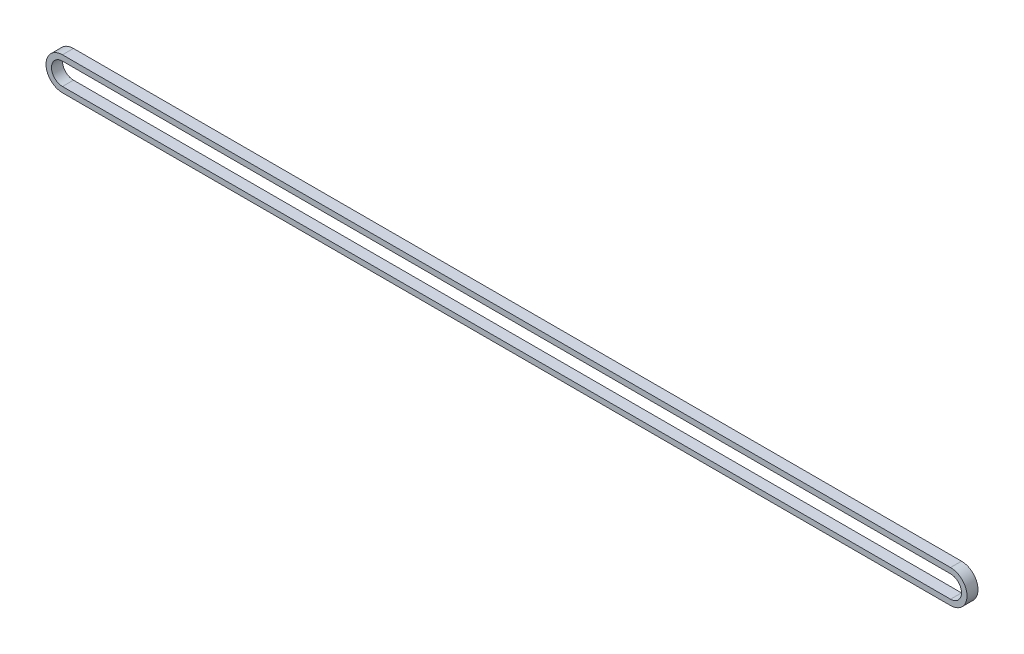
SolidWorks part; units mm, degrees
ref_plane "前视基准面" through (0, 0, 0) normal (0, 0, 1) x (1, 0, 0)
ref_plane "上视基准面" through (0, 0, 0) normal (0, 1, 0) x (1, 0, 0)
ref_plane "右视基准面" through (0, 0, 0) normal (1, 0, 0) x (0, 0, -1)
sketch "Sketch1" plane through (0, 0, 0) normal (0, 0, 1) x (1, 0, 0)
  line L0 (0, 0) -> (0, 35.8552) construction
  line L1 (-242.5, 9) -> (242.5, 9)
  line L2 (242.5, -9) -> (-242.5, -9)
  line L3 (-242.5, -6) -> (242.5, -6)
  line L4 (242.5, 6) -> (-242.5, 6)
  arc A0 (-242.5, 6) -> (-242.5, -6) centre (-242.5, 0) ccw
  arc A1 (-242.5, 9) -> (-242.5, -9) centre (-242.5, 0) ccw
  arc A2 (242.5, 9) -> (242.5, -9) centre (242.5, 0) cw
  arc A3 (242.5, 6) -> (242.5, -6) centre (242.5, 0) cw
  dimension "D1" = 12
  dimension "D2" = 3
  dimension "D3" = 242.5
extrude "Boss-Extrude1" add sketch "Sketch1" along normal blind 6
